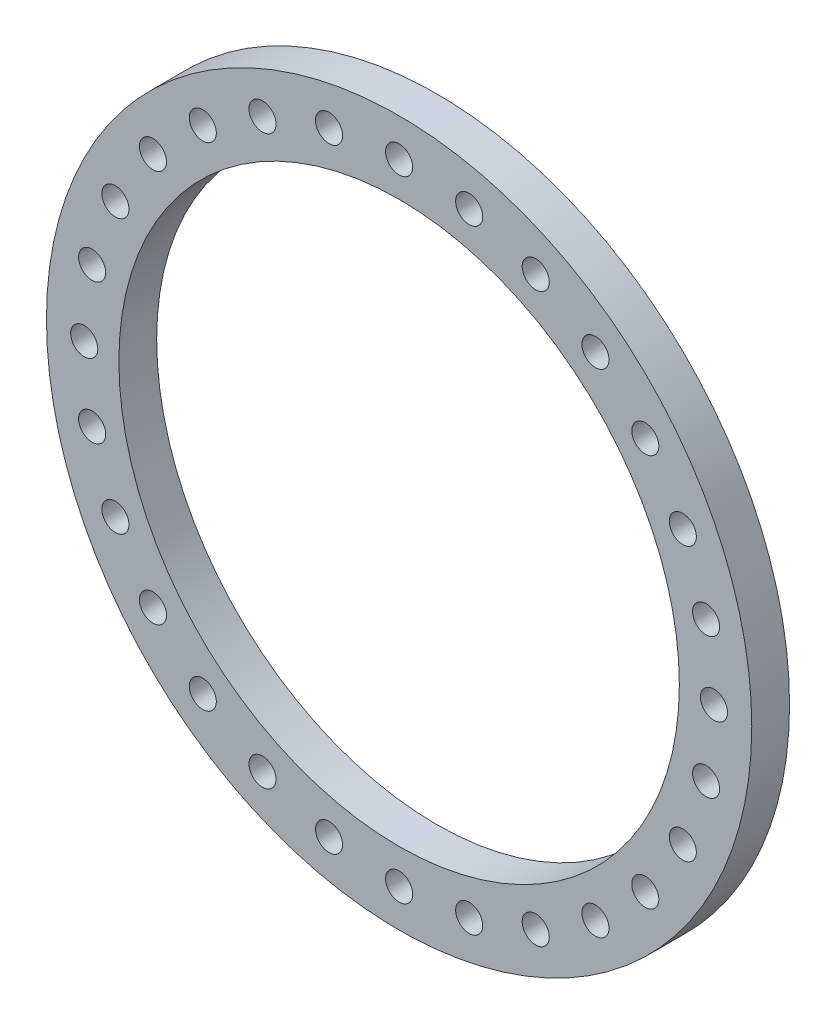
SolidWorks part; units mm, degrees
ref_plane "前视基准面" through (0, 0, 0) normal (0, 0, 1) x (1, 0, 0)
ref_plane "上视基准面" through (0, 0, 0) normal (0, 1, 0) x (1, 0, 0)
ref_plane "右视基准面" through (0, 0, 0) normal (1, 0, 0) x (0, 0, -1)
other "Configuration Table"
ref_plane "基准面1" through (0, 0, 0) normal (0, 0, -1) x (-1, 0, 0)
sketch "草图1" plane through (0, 0, 0) normal (0, 0, -1) x (-1, 0, 0)
  circle A0 centre (11.126, 48.7464) radius 2.15
  circle A1 centre (21.6942, 45.0484) radius 2.15
  circle A2 centre (31.1745, 39.0916) radius 2.15
  circle A3 centre (39.0916, 31.1745) radius 2.15
  circle A4 centre (45.0484, 21.6942) radius 2.15
  circle A5 centre (48.7464, 11.126) radius 2.15
  circle A6 centre (50, 0) radius 2.15
  circle A7 centre (48.7464, -11.126) radius 2.15
  circle A8 centre (45.0484, -21.6942) radius 2.15
  circle A9 centre (39.0916, -31.1745) radius 2.15
  circle A10 centre (31.1745, -39.0916) radius 2.15
  circle A11 centre (21.6942, -45.0484) radius 2.15
  circle A12 centre (11.126, -48.7464) radius 2.15
  circle A13 centre (0, -50) radius 2.15
  circle A14 centre (-11.126, -48.7464) radius 2.15
  circle A15 centre (-21.6942, -45.0484) radius 2.15
  circle A16 centre (-31.1745, -39.0916) radius 2.15
  circle A17 centre (-39.0916, -31.1745) radius 2.15
  circle A18 centre (-45.0484, -21.6942) radius 2.15
  circle A19 centre (-48.7464, -11.126) radius 2.15
  circle A20 centre (-50, 0) radius 2.15
  circle A21 centre (-48.7464, 11.126) radius 2.15
  circle A22 centre (-45.0484, 21.6942) radius 2.15
  circle A23 centre (-39.0916, 31.1745) radius 2.15
  circle A24 centre (-31.1745, 39.0916) radius 2.15
  circle A25 centre (-21.6942, 45.0484) radius 2.15
  circle A26 centre (-11.126, 48.7464) radius 2.15
  circle A27 centre (0, 50) radius 2.15
  circle A28 centre (0, 0) radius 44.5
  circle A29 centre (0, 0) radius 56
extrude "凸台-拉伸1" add sketch "草图1" against normal blind 6
